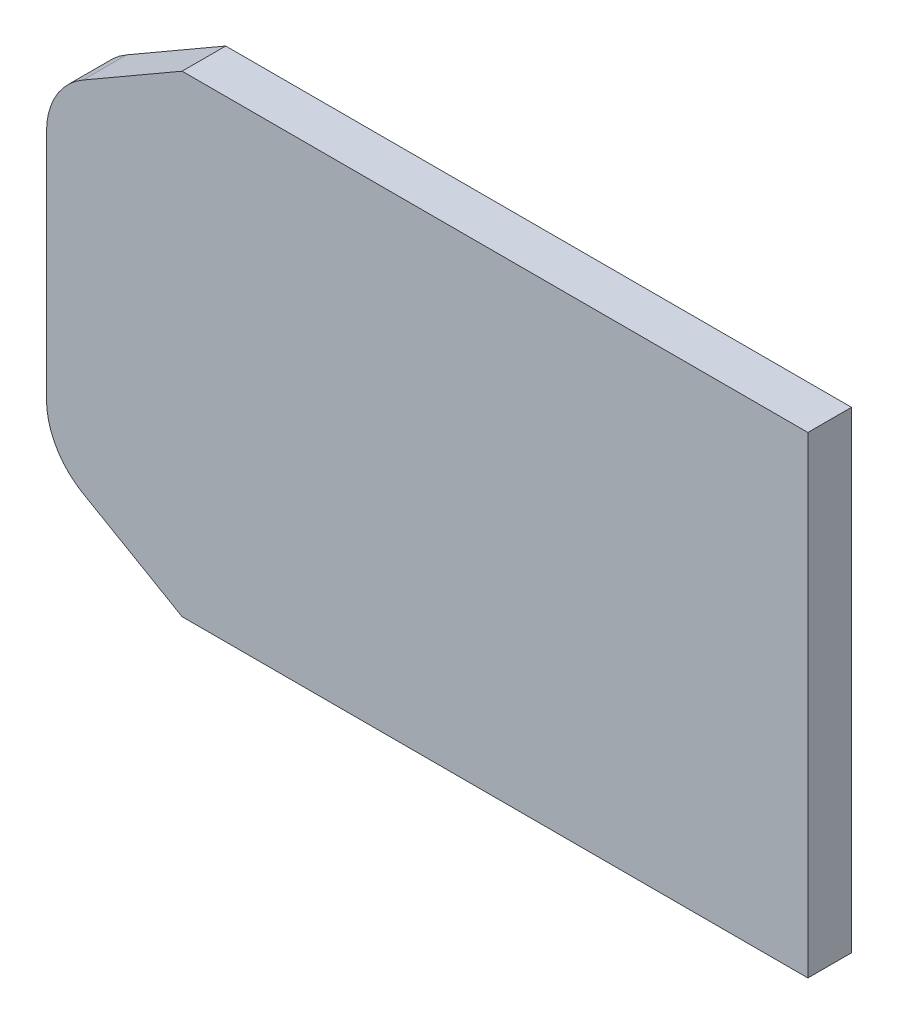
SolidWorks part; units mm, degrees
ref_plane "Front Plane" through (0, 0, 0) normal (0, 0, 1) x (1, 0, 0)
ref_plane "Top Plane" through (0, 0, 0) normal (0, 1, 0) x (1, 0, 0)
ref_plane "Right Plane" through (0, 0, 0) normal (1, 0, 0) x (0, 0, -1)
sketch "Sketch1" plane through (0, 0, 0) normal (0, 0, 1) x (1, 0, 0)
  line L0 (-37.7876, 307.9326) -> (-123.8876, 307.9326)
  line L1 (-142.5453, 259.4776) -> (-142.5453, 291.3876)
  line L7 (-37.7876, 242.9326) -> (-123.8876, 242.9326)
  line L8 (-123.8876, 242.9326) -> (-137.5451, 250.8172)
  line L10 (-123.8876, 307.9326) -> (-137.5451, 300.048)
  line L13 (-37.7876, 242.9326) -> (-37.7876, 307.9326)
  arc A0 (-137.5451, 300.048) -> (-142.5453, 291.3876) centre (-132.5453, 291.3876) ccw
  arc A3 (-137.5451, 250.8172) -> (-142.5453, 259.4776) centre (-132.5453, 259.4776) cw
  point P6 (-120.8997, 283.7282)
  point P7 (-115.0593, 246.3198)
  point P12 (0, 0)
  point P14 (0, 0)
  point P16 (0, 0)
  point P18 (15.2756, 0.8198)
  dimension "D7" = 15.77
  dimension "D9" = 10
  dimension "D10" = 10
  dimension "D1" = 15.77
  dimension "D2" = 65
  dimension "D3" = 86.1
  dimension "D4" = 86.1
  dimension "D5" = 90
  dimension "D6" = 90
  dimension "D8" = 31.91
  dimension "D11" = 242.9326
  dimension "D12" = 37.7876
  dimension "D16" = 242.9326
extrude "Boss-Extrude1" add sketch "Sketch1" along normal blind 6 separate body
